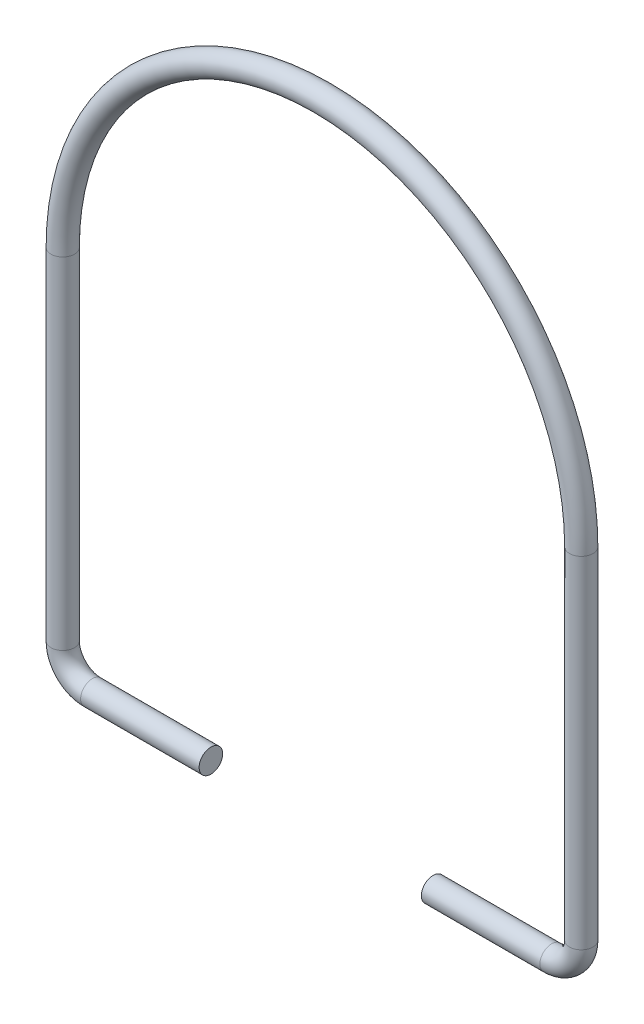
SolidWorks part; units mm, degrees
ref_plane "Front Plane" through (0, 0, 0) normal (0, 0, 1) x (1, 0, 0)
ref_plane "Top Plane" through (0, 0, 0) normal (0, 1, 0) x (1, 0, 0)
ref_plane "Right Plane" through (0, 0, 0) normal (1, 0, 0) x (0, 0, -1)
sketch "Sketch1" plane through (0, 0, 0) normal (0, 0, 1) x (1, 0, 0)
  line L0 (0, 0) -> (-16, 0)
  line L1 (-20, 4) -> (-20, 50)
  line L3 (50, 50) -> (50, 4)
  line L4 (46, 0) -> (30, 0)
  arc A0 (50, 50) -> (-20, 50) centre (15, 50) ccw
  arc A1 (50, 4) -> (46, 0) centre (46, 4) cw
  arc A2 (-20, 4) -> (-16, 0) centre (-16, 4) ccw
  point P10 (50, 0)
  point P13 (-20, 0)
  dimension "D1" = 50
  dimension "D4" = 35
  dimension "D5" = 4
  dimension "D2" = 20
  dimension "D3" = 20
  dimension "D6" = 15
sketch "Sketch2" plane through (0, 0, 0) normal (1, 0, 0) x (0, 0, -1)
  circle A0 centre (0, 0) radius 1.5875
  dimension "D1" = 3.175
sweep "Sweep1" add profiles "Sketch2" path "Sketch1"
